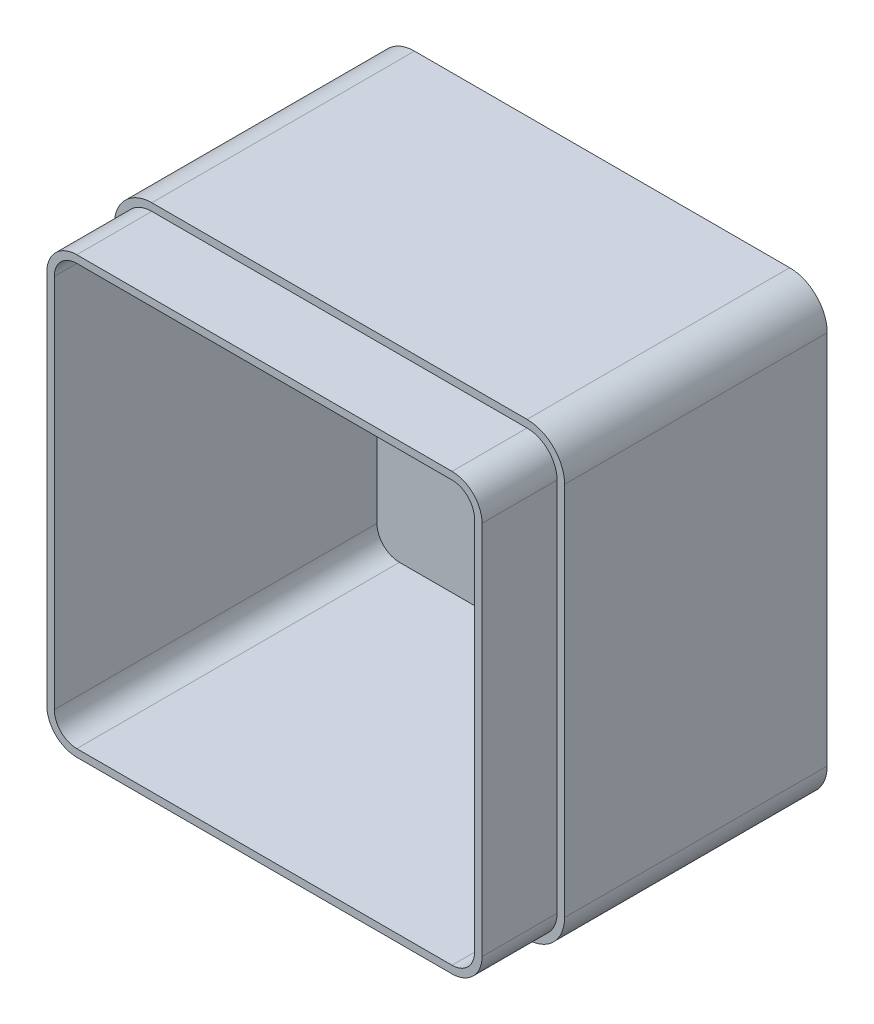
SolidWorks part; units mm, degrees
ref_plane "Front Plane" through (0, 0, 0) normal (0, 0, 1) x (1, 0, 0)
ref_plane "Top Plane" through (0, 0, 0) normal (0, 1, 0) x (1, 0, 0)
ref_plane "Right Plane" through (0, 0, 0) normal (1, 0, 0) x (0, 0, -1)
sketch "Sketch1" plane through (0, 0, 0) normal (0, 0, 1) x (1, 0, 0)
  line L1 (60, -60) -> (-60, -60)
  line L2 (60, -60) -> (60, 60)
  line L3 (60, 60) -> (-60, 60)
  line L4 (-60, -60) -> (-60, 60)
  line L5 (60, -60) -> (-60, 60) construction
  line L6 (60, 60) -> (-60, -60) construction
  point P0 (0, 0)
  dimension "D1" = 120
  dimension "D2" = 120
extrude "Boss-Extrude1" add sketch "Sketch1" along normal blind 90
fillet "Fillet1" radius 10 4 edges at (-60, 60, 45) (-60, -60, 45) (60, -60, 45) (60, 60, 45)
shell "Shell1" thickness 4
sketch "Sketch2" plane through (0, 0, 90) normal (0, 0, 1) x (1, 0, 0)
  line L0 (50, 58) -> (-50, 58)
  line L1 (-58, 50) -> (-58, -50)
  line L2 (-50, -58) -> (50, -58)
  line L3 (58, -50) -> (58, 50)
  line L4 (50, 60) -> (-50, 60)
  line L5 (-60, 50) -> (-60, -50)
  line L6 (-50, -60) -> (50, -60)
  line L7 (60, -50) -> (60, 50)
  line L8 (50, 60) -> (-50, 60)
  line L9 (-60, 50) -> (-60, -50)
  line L10 (-50, -60) -> (50, -60)
  line L11 (60, -50) -> (60, 50)
  arc A0 (-50, 58) -> (-58, 50) centre (-50, 50) ccw
  arc A1 (-58, -50) -> (-50, -58) centre (-50, -50) ccw
  arc A2 (50, -58) -> (58, -50) centre (50, -50) ccw
  arc A3 (58, 50) -> (50, 58) centre (50, 50) ccw
  arc A4 (-50, 60) -> (-60, 50) centre (-50, 50) ccw
  arc A5 (-60, -50) -> (-50, -60) centre (-50, -50) ccw
  arc A6 (50, -60) -> (60, -50) centre (50, -50) ccw
  arc A7 (60, 50) -> (50, 60) centre (50, 50) ccw
  arc A8 (-50, 60) -> (-60, 50) centre (-50, 50) ccw
  arc A9 (-60, -50) -> (-50, -60) centre (-50, -50) ccw
  arc A10 (50, -60) -> (60, -50) centre (50, -50) ccw
  arc A11 (60, 50) -> (50, 60) centre (50, 50) ccw
  dimension "D1" = 0
  dimension "D2" = 2
extrude "Cut-Extrude1" cut sketch "Sketch2" against normal blind 20
